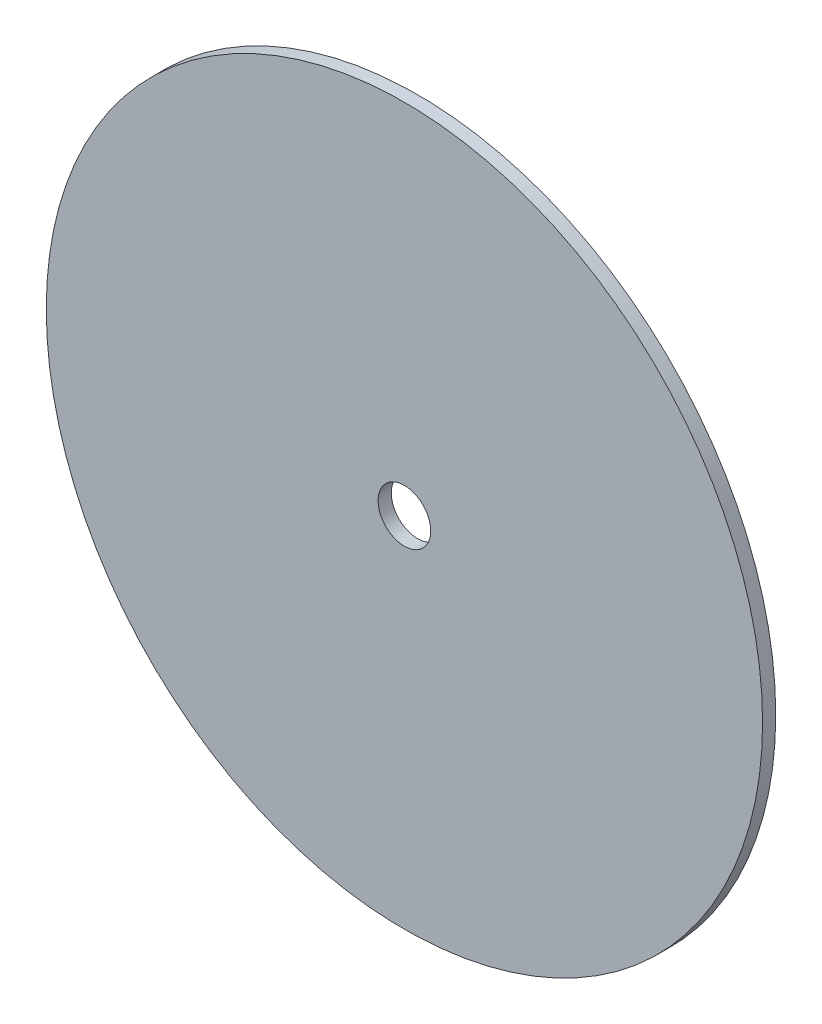
SolidWorks part; units mm, degrees
material "ABS PC"
ref_plane "Front Plane" through (0, 0, 0) normal (0, 0, 1) x (1, 0, 0)
ref_plane "Top Plane" through (0, 0, 0) normal (0, 1, 0) x (1, 0, 0)
ref_plane "Right Plane" through (0, 0, 0) normal (1, 0, 0) x (0, 0, -1)
sketch "Sketch1" plane through (0, 0, 0) normal (0, 0, 1) x (1, 0, 0)
  circle A0 centre (0, 0) radius 43.18
  circle A1 centre (0, 0) radius 3.175
  dimension "D1" = 86.36
  dimension "D2" = 6.35
extrude "Boss-Extrude1" add sketch "Sketch1" along normal blind 1.5875
equation "\"A\"= 3.4"
equation "\"D1@Sketch1\"=\"A\""
